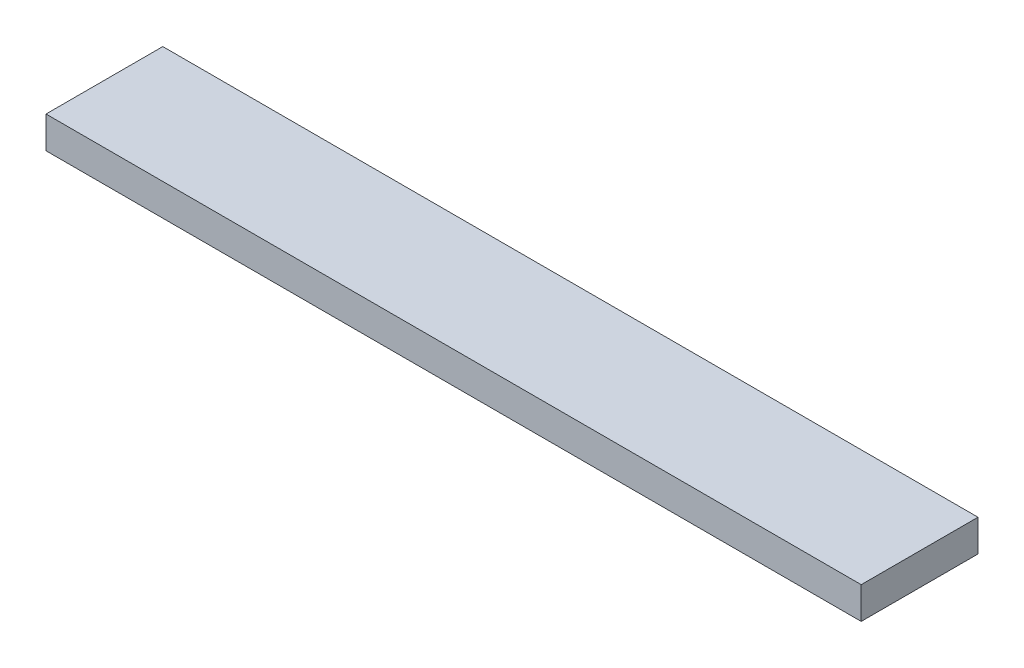
SolidWorks part; units mm, degrees
material "Low Carbon Steel"
ref_plane "Front Plane" through (0, 0, 0) normal (0, 0, 1) x (1, 0, 0)
ref_plane "Top Plane" through (0, 0, 0) normal (0, 1, 0) x (1, 0, 0)
ref_plane "Right Plane" through (0, 0, 0) normal (1, 0, 0) x (0, 0, -1)
sketch "Sketch1" plane through (0, 0, 0) normal (0, 1, 0) x (1, 0, 0)
  line L1 (0, 0) -> (975, 0)
  line L2 (0, 0) -> (0, 139.7)
  line L3 (0, 139.7) -> (975, 139.7)
  line L4 (975, 0) -> (975, 139.7)
  dimension "D1" = 975
  dimension "D2" = 139.7
extrude "Boss-Extrude1" add sketch "Sketch1" along normal blind 38.1
other "Freeze***"
